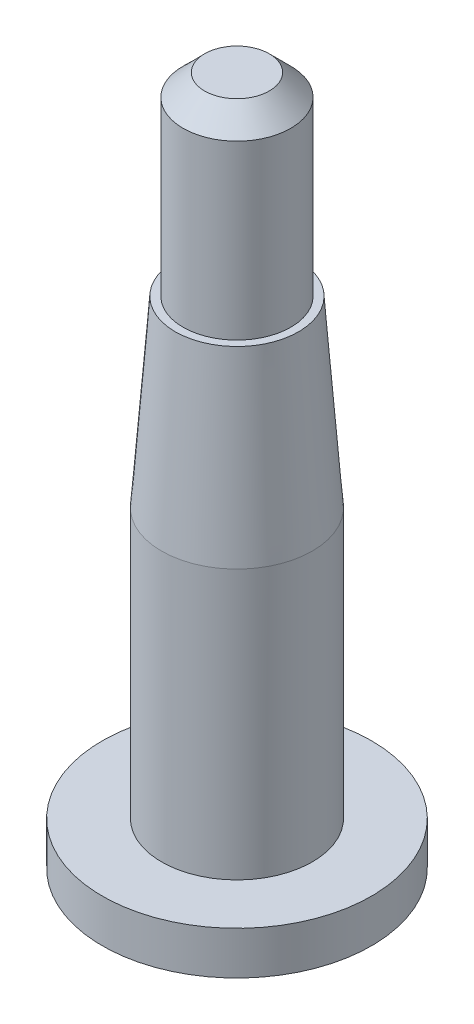
SolidWorks part; units mm, degrees
ref_plane "Front Plane" through (0, 0, 0) normal (0, 0, 1) x (1, 0, 0)
ref_plane "Top Plane" through (0, 0, 0) normal (0, 1, 0) x (1, 0, 0)
ref_plane "Right Plane" through (0, 0, 0) normal (1, 0, 0) x (0, 0, -1)
sketch "Sketch2" plane through (0, 0, 0) normal (0, 1, 0) x (1, 0, 0)
  circle A0 centre (0, 0) radius 7
  dimension "D1" = 14
extrude "Boss-Extrude1" add sketch "Sketch2" along normal blind 25
sketch "Sketch3" plane through (0, 25, 0) normal (0, 1, 0) x (1, 0, 0)
  circle A1 centre (0, 0) radius 7
  circle A2 centre (0, 0) radius 7
  dimension "D1" = 0
extrude "Boss-Extrude2" add sketch "Sketch3" along normal blind 17 draft 4.289
sketch "Sketch4" plane through (0, 42, 0) normal (0, 1, 0) x (1, 0, 0)
  circle A0 centre (0, 0) radius 5
  dimension "D1" = 10
extrude "Boss-Extrude3" add sketch "Sketch4" along normal blind 18
cosmetic thread "Cosmetic Thread2" parameters "D1"=16, "D2"=8.891
chamfer "Chamfer1" distance 2 angle 45 1 edges at (0, 60, 5)
sketch "Sketch5" plane through (0, 0, 0) normal (0, -1, 0) x (1, 0, 0)
  circle A0 centre (0, 0) radius 12.5
  dimension "D1" = 25
extrude "Boss-Extrude4" add sketch "Sketch5" along normal blind 4
